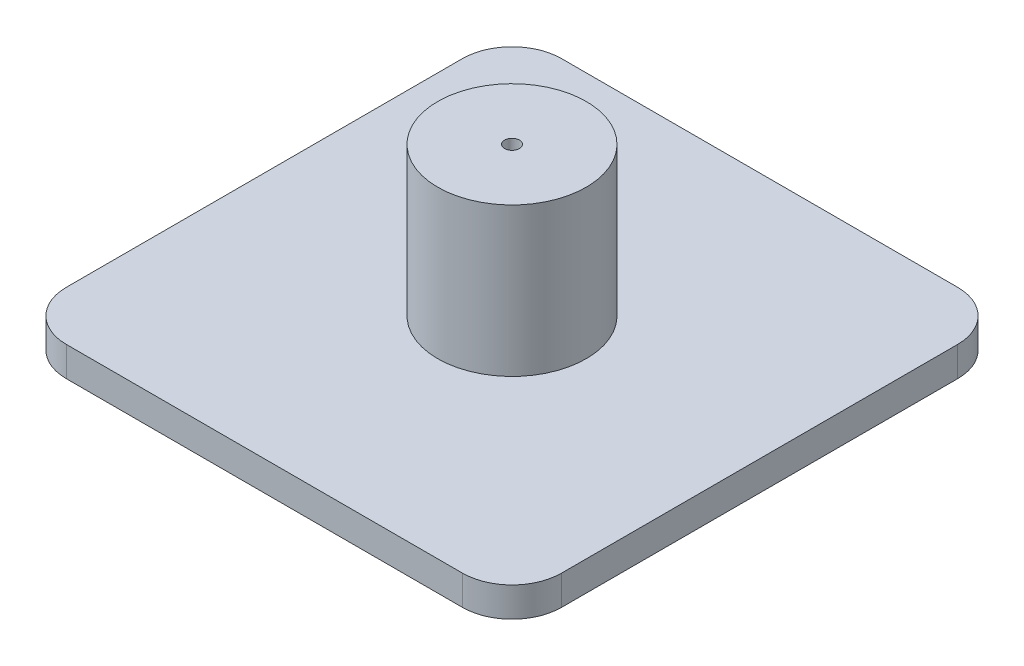
SolidWorks part; units mm, degrees
ref_plane "Piano frontale" through (0, 0, 0) normal (0, 0, 1) x (1, 0, 0)
ref_plane "Piano superiore" through (0, 0, 0) normal (0, 1, 0) x (1, 0, 0)
ref_plane "Piano destro" through (0, 0, 0) normal (1, 0, 0) x (0, 0, -1)
sketch "Schizzo1" plane through (0, 0, 0) normal (0, 1, 0) x (1, 0, 0)
  line L1 (-15.8085, 18.6827) -> (34.1915, 18.6827)
  line L2 (-15.8085, 18.6827) -> (-15.8085, -31.3173)
  line L3 (-15.8085, -31.3173) -> (34.1915, -31.3173)
  line L4 (34.1915, 18.6827) -> (34.1915, -31.3173)
  dimension "D1" = 50
  dimension "D2" = 50
extrude "Estrusione-Estrusione1" add sketch "Schizzo1" along normal blind 3
fillet "Raccordo1" radius 5 4 edges at (-15.8085, 1.5, -18.6827) (-15.8085, 1.5, 31.3173) (34.1915, 1.5, -18.6827) (34.1915, 1.5, 31.3173)
sketch "Schizzo2" plane through (0, 3, 0) normal (0, 1, 0) x (1, 0, 0)
  line L0 (34.1915, -26.3173) -> (34.1915, 13.6827) construction
  line L1 (29.1915, 18.6827) -> (-10.8085, 18.6827) construction
  circle A0 centre (9.1915, -6.3173) radius 7.5
  dimension "D1" = 15
  dimension "D2" = 25
  dimension "D3" = 25
extrude "Estrusione-Estrusione2" add sketch "Schizzo2" along normal blind 15
sketch "Schizzo3" plane through (0, 18, 0) normal (0, 1, 0) x (1, 0, 0)
  circle A0 centre (9.1915, -6.3173) radius 0.75
  circle A1 centre (9.1915, -6.3173) radius 7.5 construction
  dimension "D1" = 1.5
  dimension "D2" = 0
extrude "Taglio-Estrusione1" cut sketch "Schizzo3" against normal through all
